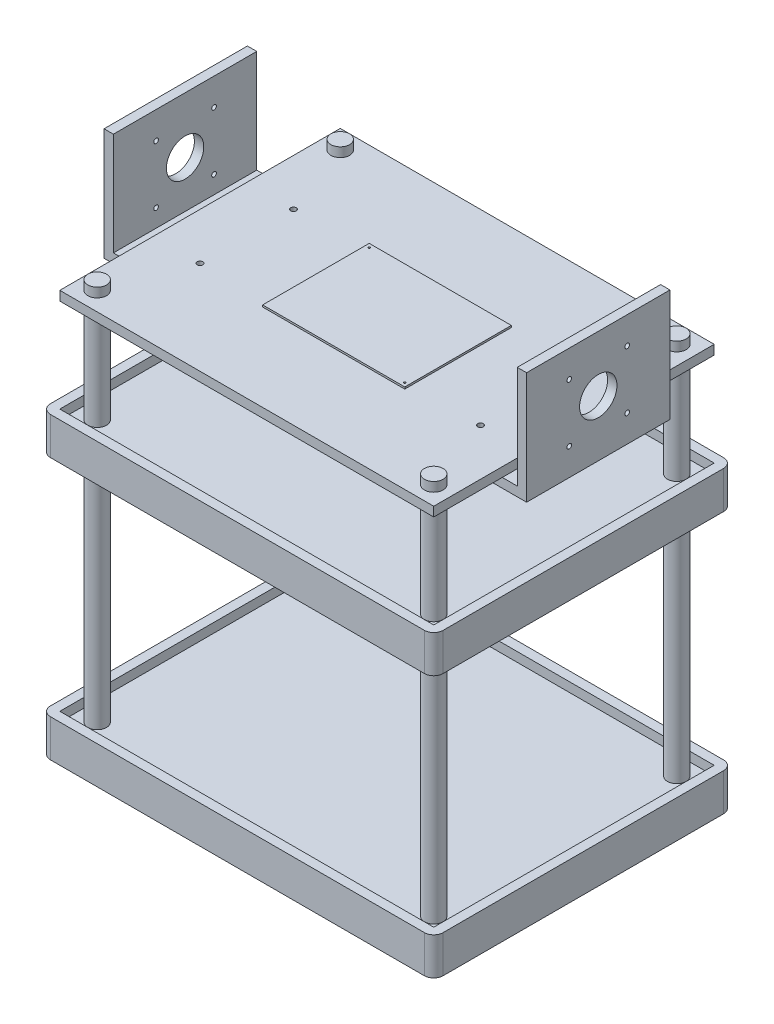
SolidWorks part; units mm, degrees
ref_plane "Front Plane" through (0, 0, 0) normal (0, 0, 1) x (1, 0, 0)
ref_plane "Top Plane" through (0, 0, 0) normal (0, 1, 0) x (1, 0, 0)
ref_plane "Right Plane" through (0, 0, 0) normal (1, 0, 0) x (0, 0, -1)
sketch "Sketch1" plane through (0, 0, 0) normal (0, 1, 0) x (1, 0, 0)
  line L1 (-100, 75) -> (100, 75)
  line L2 (-100, 75) -> (-100, -75)
  line L3 (-100, -75) -> (100, -75)
  line L4 (100, 75) -> (100, -75)
  line L5 (-100, 75) -> (100, -75) construction
  line L6 (-100, -75) -> (100, 75) construction
  point P0 (0, 0)
  dimension "D1" = 200
  dimension "D2" = 150
extrude "Boss-Extrude1" add sketch "Sketch1" along normal blind 5
sketch "Sketch2" plane through (0, 5, 0) normal (0, 1, 0) x (1, 0, 0)
  line L0 (-100, 75) -> (-100, -75) construction
  line L1 (100, 75) -> (-100, 75) construction
  line L2 (0, 73.0671) -> (0, 83.6614) construction
  line L3 (0, 83.6614) -> (0, -94.4748) construction
  line L4 (-110.8687, 0) -> (113.9791, 0) construction
  circle A0 centre (-90, 65) radius 5
  circle A1 centre (90, 65) radius 5
  circle A2 centre (90, -65) radius 5
  circle A3 centre (-90, -65) radius 5
  dimension "D1" = 10
  dimension "D2" = 10
  dimension "D3" = 10
extrude "Cut-Extrude1" cut sketch "Sketch2" against normal blind 10
ref_plane "Plane1" through (0, 140, 0) normal (0, 1, 0) x (1, 0, 0)
sketch "Sketch3" plane through (0, 140, 0) normal (0, 1, 0) x (1, 0, 0)
  line L1 (-100, 75) -> (100, 75)
  line L2 (-100, 75) -> (-100, -75)
  line L3 (-100, -75) -> (100, -75)
  line L4 (100, 75) -> (100, -75)
  line L5 (-100, 75) -> (100, -75) construction
  line L6 (-100, -75) -> (100, 75) construction
  circle A0 centre (-90, 65) radius 5
  circle A1 centre (90, 65) radius 5
  circle A2 centre (-90, -65) radius 5
  circle A3 centre (90, -65) radius 5
  point P0 (0, 0)
extrude "Boss-Extrude2" add sketch "Sketch3" along normal blind 5 separate body
ref_plane "Plane4" through (0, 200, 0) normal (0, 1, 0) x (1, 0, 0)
sketch "Sketch4" plane through (0, 200, 0) normal (0, 1, 0) x (1, 0, 0)
  line L1 (-100, 75) -> (100, 75)
  line L2 (-100, 75) -> (-100, -75)
  line L3 (-100, -75) -> (100, -75)
  line L4 (100, 75) -> (100, -75)
  line L5 (-100, 75) -> (100, -75) construction
  line L6 (-100, -75) -> (100, 75) construction
  circle A0 centre (-90, 65) radius 5
  circle A1 centre (90, 65) radius 5
  circle A2 centre (90, -65) radius 5
  circle A3 centre (-90, -65) radius 5
  point P1 (0, 0)
extrude "Boss-Extrude3" add sketch "Sketch4" along normal blind 5 separate body
sketch "Sketch5" plane through (0, 205, 0) normal (0, 1, 0) x (1, 0, 0)
  circle A0 centre (-90, -65) radius 5
sketch "Sketch17" plane through (0, 200, 0) normal (0, -1, 0) x (1, 0, 0)
  circle A0 centre (-90, -65) radius 5.3637
sketch "Sketch21" plane through (0, 5, 0) normal (0, 1, 0) x (1, 0, 0)
  circle A0 centre (-90, -65) radius 5
  circle A1 centre (-90, 65) radius 5
  circle A2 centre (90, 65) radius 5
  circle A3 centre (90, -65) radius 5
  dimension "D1" = 10
  dimension "D2" = 10
  dimension "D3" = 10
  dimension "D4" = 10
extrude "Boss-Extrude13" add sketch "Sketch21" along normal blind 205
sketch "Sketch22" plane through (0, 5, 0) normal (0, 1, 0) x (1, 0, 0)
  circle A0 centre (-90, 65) radius 5
  circle A1 centre (-90, -65) radius 5
  circle A2 centre (90, -65) radius 5
  circle A3 centre (90, 65) radius 5
  dimension "D1" = 10
  dimension "D2" = 10
  dimension "D3" = 10
  dimension "D4" = 10
extrude "Boss-Extrude14" add sketch "Sketch22" against normal blind 15
sketch "Sketch23" plane through (0, 205, 0) normal (0, 1, 0) x (1, 0, 0)
  line L0 (-100, 75) -> (-100, -75) construction
  line L1 (-140.155, 0) -> (119.4256, 0) construction
  line L2 (0, -2.75) -> (0, 2.75) construction
  circle A0 centre (-75, 25) radius 1.5
  circle A1 centre (-75, -25) radius 1.5
  circle A2 centre (75, -25) radius 1.5
  circle A3 centre (75, 25) radius 1.5
  dimension "D1" = 3
  dimension "D2" = 25
  dimension "D3" = 25
extrude "Cut-Extrude2" cut sketch "Sketch23" against normal blind 10
sketch "Sketch27" plane through (0, 205, 0) normal (0, 1, 0) x (1, 0, 0)
  line L0 (-38, 28.5) -> (38, -28.5) construction
  line L5 (-38, -28.5) -> (38, 28.5) construction
  line L7 (-38, 28.5) -> (38, 28.5)
  line L8 (-38, 28.5) -> (-38, -28.5)
  line L9 (-38, -28.5) -> (38, -28.5)
  line L10 (38, 28.5) -> (38, -28.5)
  circle A0 centre (-36, 26.5) radius 0.5
  circle A1 centre (36, -26.5) radius 0.5
  point P0 (-6.164, -10.787)
  point P5 (0, 0)
  point P11 (0, 0)
  dimension "D3" = 1
  dimension "D6" = 1
  dimension "D1" = 57
  dimension "D2" = 76
  dimension "D4" = 2
  dimension "D5" = 2
  dimension "D7" = 2
  dimension "D8" = 2
extrude "Boss-Extrude16" add sketch "Sketch27" along normal blind 1 contours L8 L7 L10 L9
sketch "Sketch30" plane through (0, 206, 0) normal (0, 1, 0) x (1, 0, 0)
  line L0 (-38, 28.5) -> (-38, -28.5) construction
  line L1 (-38, 28.5) -> (38, 28.5) construction
  line L2 (38, 28.5) -> (38, -28.5) construction
  line L3 (-38, -28.5) -> (38, -28.5) construction
  circle A0 centre (-36, 26.5) radius 0.5
  circle A1 centre (36, -26.5) radius 0.5
  dimension "D1" = 1
  dimension "D4" = 1
  dimension "D2" = 2
  dimension "D3" = 2
  dimension "D5" = 2
  dimension "D6" = 2
extrude "Cut-Extrude3" cut sketch "Sketch30" against normal blind 30
sketch "Sketch35" plane through (0, 0, 0) normal (0, -1, 0) x (-1, 0, 0)
  line L1 (100, -75) -> (-100, -75)
  line L2 (100, -75) -> (100, 75)
  line L3 (100, 75) -> (-100, 75)
  line L4 (-100, -75) -> (-100, 75)
  line L5 (100, -75) -> (-100, 75) construction
  line L6 (100, 75) -> (-100, -75) construction
  line L7 (105, -80) -> (-105, -80)
  line L8 (105, -80) -> (105, 80)
  line L9 (105, 80) -> (-105, 80)
  line L10 (-105, -80) -> (-105, 80)
  line L11 (105, -80) -> (-105, 80) construction
  line L12 (105, 80) -> (-105, -80) construction
  point P0 (0, 0)
  point P6 (0, 0)
  dimension "D1" = 150
  dimension "D2" = 160
  dimension "D3" = 200
  dimension "D4" = 210
extrude "Boss-Extrude19" add sketch "Sketch35" along normal mid plane 20 separate body
fillet "Fillet4" radius 5 4 edges at (105, 0, 80) (105, 0, -80) (-105, 0, 80) (-105, 0, -80)
sketch "Sketch39" plane through (0, 140, 0) normal (0, -1, 0) x (1, 0, 0)
  line L1 (-100, 75) -> (100, 75)
  line L2 (-100, 75) -> (-100, -75)
  line L3 (-100, -75) -> (100, -75)
  line L4 (100, 75) -> (100, -75)
  line L5 (-100, 75) -> (100, -75) construction
  line L6 (-100, -75) -> (100, 75) construction
  line L7 (-105, 80) -> (105, 80)
  line L8 (-105, 80) -> (-105, -80)
  line L9 (-105, -80) -> (105, -80)
  line L10 (105, 80) -> (105, -80)
  line L11 (-105, 80) -> (105, -80) construction
  line L12 (-105, -80) -> (105, 80) construction
  point P0 (0, 0)
  point P6 (0, 0)
  dimension "D1" = 150
  dimension "D2" = 200
  dimension "D3" = 160
  dimension "D4" = 210
extrude "Boss-Extrude20" add sketch "Sketch39" along normal mid plane 20 separate body
fillet "Fillet5" radius 5 4 edges at (105, 140, 80) (105, 140, -80) (-105, 140, -80) (-105, 140, 80)
sketch "Sketch42" plane through (0, 200, 0) normal (0, -1, 0) x (1, 0, 0)
  line L1 (-7.5, 10) -> (7.5, 10)
  line L2 (-7.5, 10) -> (-7.5, -10)
  line L3 (-7.5, -10) -> (7.5, -10)
  line L4 (7.5, 10) -> (7.5, -10)
  line L5 (-7.5, 10) -> (7.5, -10) construction
  line L6 (-7.5, -10) -> (7.5, 10) construction
  line L7 (-70.7403, -17.1967) -> (-45.7403, -17.1967)
  line L8 (-70.7403, -17.1967) -> (-70.7403, 32.8033)
  line L9 (-70.7403, 32.8033) -> (-45.7403, 32.8033)
  line L10 (-45.7403, -17.1967) -> (-45.7403, 32.8033)
  line L11 (-70.7403, -17.1967) -> (-45.7403, 32.8033) construction
  line L12 (-70.7403, 32.8033) -> (-45.7403, -17.1967) construction
  line L13 (15.7, 23.8618) -> (59, 23.8618)
  line L14 (15.7, 23.8618) -> (15.7, -19.4382)
  line L15 (15.7, -19.4382) -> (59, -19.4382)
  line L16 (59, 23.8618) -> (59, -19.4382)
  line L17 (15.7, 23.8618) -> (59, -19.4382) construction
  line L18 (15.7, -19.4382) -> (59, 23.8618) construction
  point P0 (0, 0)
  point P6 (-58.2403, 7.8033)
  point P11 (37.35, 2.2118)
  dimension "D1" = 20
  dimension "D2" = 15
  dimension "D3" = 50
  dimension "D4" = 25
  dimension "D5" = 43.3
  dimension "D6" = 43.3
  dimension "D7" = 8.2
extrude "Boss-Extrude23" add sketch "Sketch42" along normal blind 1
sketch "Sketch46" plane through (0, 200, 0) normal (0, -1, 0) x (-1, 0, 0)
  line L0 (-196.0871, 0) -> (303.0775, 0) construction
  line L5 (100, -75) -> (100, 75) construction
  line L6 (0, 82.5) -> (0, -82.5) construction
  line L7 (-108, 38.3353) -> (-108, -38.3353)
  line L8 (78, 38.3353) -> (108, 38.3353)
  line L9 (78, 38.3353) -> (78, -38.3353)
  line L10 (78, -38.3353) -> (108, -38.3353)
  line L11 (108, 38.3353) -> (108, -38.3353)
  line L12 (78, 38.3353) -> (108, -38.3353) construction
  line L13 (78, -38.3353) -> (108, 38.3353) construction
  line L14 (-78, -38.3353) -> (-108, -38.3353)
  line L15 (-78, 38.3353) -> (-78, -38.3353)
  line L16 (-78, 38.3353) -> (-108, 38.3353)
  point P0 (122.8294, -19.1676)
  point P6 (93, 0)
  dimension "D1" = 22
  dimension "D2" = 30
extrude "Boss-Extrude24" add sketch "Sketch46" along normal blind 5
sketch "Sketch48" plane through (-108, 0, 0) normal (-1, 0, 0) x (0, 0, 1)
  line L0 (0, 195) -> (0, 255) construction
  line L1 (-38.3353, 195) -> (38.3353, 195)
  line L2 (-38.3353, 195) -> (-38.3353, 255)
  line L3 (-38.3353, 255) -> (38.3353, 255)
  line L4 (38.3353, 195) -> (38.3353, 255)
  line L5 (-38.3353, 225) -> (38.3353, 225) construction
  line L6 (38.3353, 195) -> (38.3353, 200) construction
  circle A0 centre (-15.5, 209.5) radius 1.25
  circle A1 centre (15.5, 209.5) radius 1.25
  circle A2 centre (15.5, 240.5) radius 1.25
  circle A3 centre (-15.5, 240.5) radius 1.25
  circle A4 centre (0, 225) radius 10
  point P17 (38.3353, 195)
  dimension "D2" = 2.5
  dimension "D3" = 2.5
  dimension "D8" = 20
  dimension "D1" = 60
  dimension "D4" = 15.5
  dimension "D5" = 15.5
  dimension "D6" = 31
  dimension "D7" = 15.5
extrude "Boss-Extrude25" add sketch "Sketch48" along normal blind 5
sketch "Sketch54" plane through (108, 0, 0) normal (1, 0, 0) x (0, 0, -1)
  line L1 (-38.3353, 195) -> (38.3353, 195)
  line L2 (-38.3353, 195) -> (-38.3353, 255)
  line L3 (-38.3353, 255) -> (38.3353, 255)
  line L4 (38.3353, 195) -> (38.3353, 255)
extrude "Boss-Extrude26" add sketch "Sketch54" along normal blind 5
ref_plane "Plane5" through (0, 65, 0) normal (0, 1, 0) x (1, 0, 0)
sketch "Sketch55" plane through (113, 0, 0) normal (1, 0, 0) x (0, 0, -1)
  line L0 (-38.3353, 225) -> (38.3353, 225) construction
  line L1 (-38.3353, 255) -> (-38.3353, 195) construction
  line L2 (38.3353, 195) -> (38.3353, 255) construction
  line L3 (0, 195) -> (0, 255) construction
  line L4 (-38.3353, 195) -> (38.3353, 195) construction
  line L5 (38.3353, 255) -> (-38.3353, 255) construction
  circle A0 centre (-15.5, 209.5) radius 1.25
  circle A1 centre (15.5, 209.5) radius 1.25
  circle A2 centre (15.5, 240.5) radius 1.25
  circle A3 centre (-15.5, 240.5) radius 1.25
  circle A4 centre (0, 225) radius 10
  dimension "D1" = 2.5
  dimension "D2" = 2.5
  dimension "D7" = 20
  dimension "D3" = 15.5
  dimension "D4" = 15.5
  dimension "D5" = 15.5
  dimension "D6" = 15.5
extrude "Cut-Extrude4" cut sketch "Sketch55" against normal blind 10
